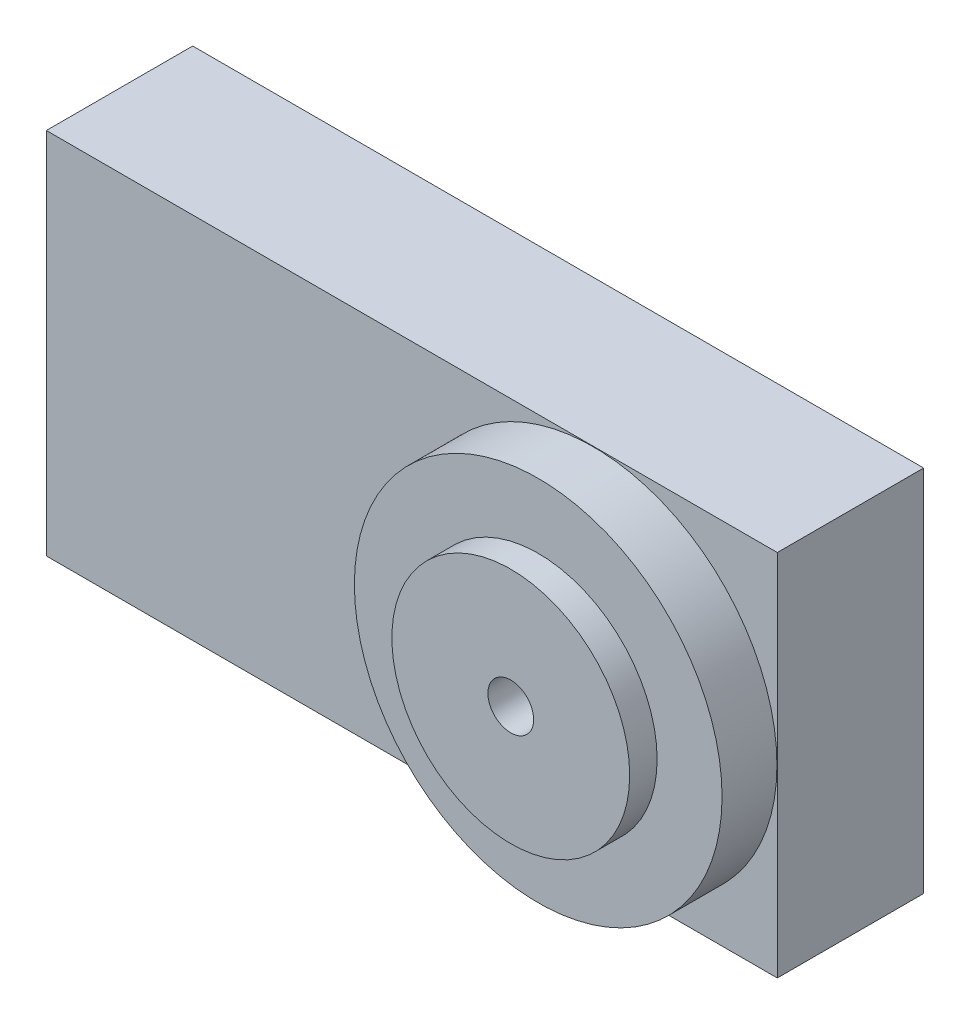
SolidWorks part; units mm, degrees
material "PBT General Purpose"
ref_plane "Front Plane" through (0, 0, 0) normal (0, 0, 1) x (1, 0, 0)
ref_plane "Top Plane" through (0, 0, 0) normal (0, 1, 0) x (1, 0, 0)
ref_plane "Right Plane" through (0, 0, 0) normal (1, 0, 0) x (0, 0, -1)
sketch "Sketch1" plane through (0, 0, 0) normal (0, 0, 1) x (1, 0, 0)
  line L0 (5.6675, -108.8958) -> (6.0233, -83.8958) construction
  line L1 (45.6675, -126.0967) -> (5.7094, -126.0967)
  line L2 (45.6675, -126.0967) -> (45.6675, -105.9531)
  line L3 (45.6675, -105.9531) -> (5.7094, -105.9531)
  line L4 (5.7094, -126.0967) -> (5.7094, -105.9531)
extrude "Boss-Extrude1" add sketch "Sketch1" along normal blind 8
sketch "Sketch2" plane through (0, 0, 8) normal (0, 0, 1) x (1, 0, 0)
  line L0 (45.6675, -126.0967) -> (45.6675, -105.9531) construction
  circle A0 centre (35.5975, -116.0249) radius 10.0498
  dimension "D1" = 10.07
extrude "Boss-Extrude2" add sketch "Sketch2" along normal blind 3
sketch "Sketch3" plane through (0, 0, 11) normal (0, 0, 1) x (1, 0, 0)
  circle A0 centre (35.5975, -116.0249) radius 6.5
  dimension "D1" = 13
extrude "Boss-Extrude3" add sketch "Sketch3" along normal blind 1.5
sketch "Sketch4" plane through (0, 0, 12.5) normal (0, 0, 1) x (1, 0, 0)
  circle A0 centre (35.5975, -116.0249) radius 1.25
  dimension "D1" = 2.5
extrude "Cut-Extrude1" cut sketch "Sketch4" against normal blind 5
cosmetic thread "Cosmetic Thread1" parameters "D1"=5, "D2"=3
